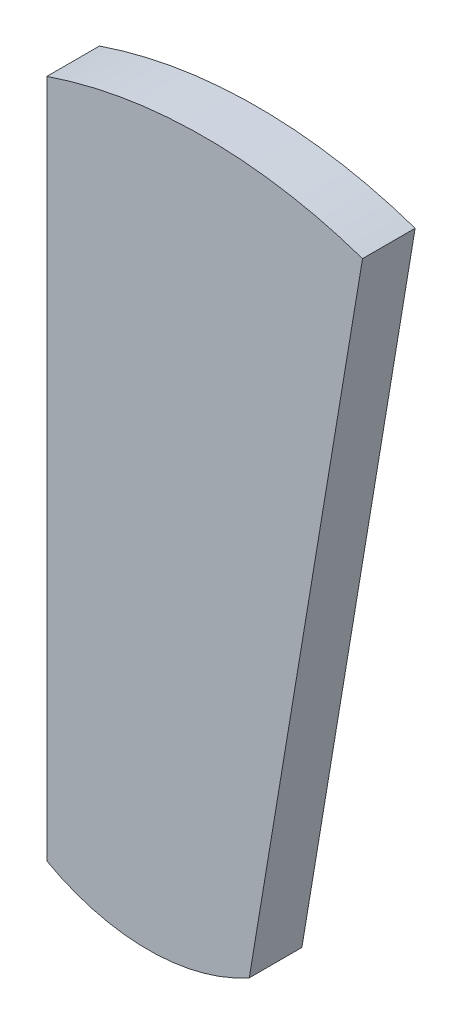
SolidWorks part; units mm, degrees
ref_plane "Front Plane" through (0, 0, 0) normal (0, 0, 1) x (1, 0, 0)
ref_plane "Top Plane" through (0, 0, 0) normal (0, 1, 0) x (1, 0, 0)
ref_plane "Right Plane" through (0, 0, 0) normal (1, 0, 0) x (0, 0, -1)
sketch "Sketch1" plane through (0, 0, 0) normal (0, 0, 1) x (1, 0, 0)
  line L0 (-36, 34.7634) -> (-36, -42.7328)
  line L1 (-36, -42.7328) -> (-12.916, -42.7328)
  line L2 (-12.916, -42.7328) -> (0, 34.7634)
  line L3 (-36, 34.7634) -> (0, 34.7634)
  arc A0 (-36, 34.7634) -> (0, 34.7634) centre (-18, -17.7336) cw
  arc A1 (-36, -42.7328) -> (-12.916, -42.7328) centre (-24.458, -22.0299) ccw
extrude "Boss-Extrude1" add sketch "Sketch1" along normal mid plane 6 contours A0 L3 | L3 L0 L1 L2 | L1 A1
